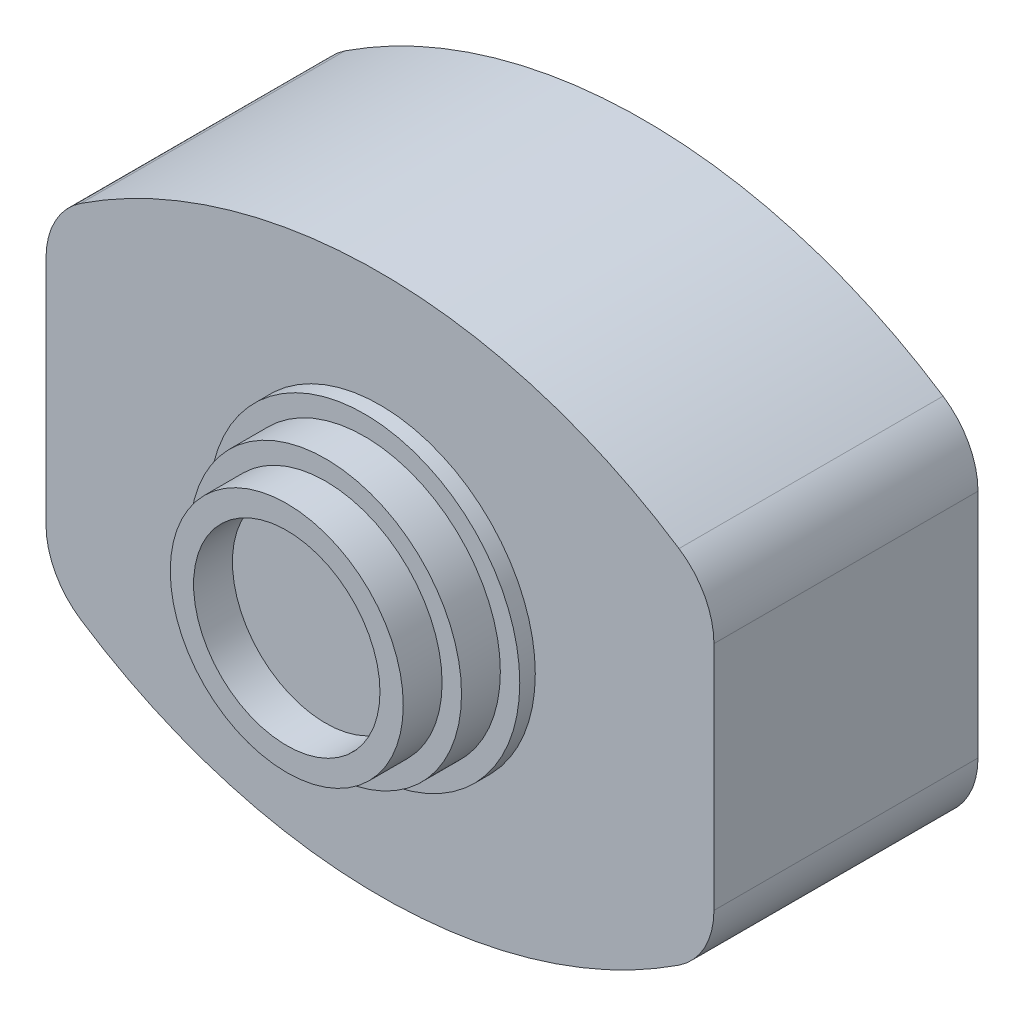
SolidWorks part; units mm, degrees
ref_plane "Front Plane" through (0, 0, 0) normal (0, 0, 1) x (1, 0, 0)
ref_plane "Top Plane" through (0, 0, 0) normal (0, 1, 0) x (1, 0, 0)
ref_plane "Right Plane" through (0, 0, 0) normal (1, 0, 0) x (0, 0, -1)
sketch "Sketch1" plane through (0, 0, 0) normal (0, 0, 1) x (1, 0, 0)
  line L1 (86, 5.126) -> (86, 34.874)
  line L3 (0, 34.874) -> (0, 5.126)
  arc A0 (4.5, 43.2257) -> (81.5, 43.2257) centre (43, -15.2359) cw
  arc A1 (4.5, -3.2257) -> (81.5, -3.2257) centre (43, 55.2359) ccw
  arc A2 (81.5, -3.2257) -> (86, 5.126) centre (76, 5.126) ccw
  arc A3 (86, 34.874) -> (81.5, 43.2257) centre (76, 34.874) ccw
  arc A4 (4.5, 43.2257) -> (0, 34.874) centre (10, 34.874) ccw
  arc A5 (4.5, -3.2257) -> (0, 5.126) centre (10, 5.126) cw
  point P15 (0, 0)
  dimension "D1" = 10
extrude "Boss-Extrude1" add sketch "Sketch1" along normal blind 34
sketch "Sketch2" plane through (0, 0, 34) normal (0, 0, 1) x (1, 0, 0)
  circle A0 centre (43, 20) radius 20
extrude "Boss-Extrude2" add sketch "Sketch2" along normal blind 2 contours A0
sketch "Sketch3" plane through (0, 0, 36) normal (0, 0, 1) x (1, 0, 0)
  circle A1 centre (43, 20) radius 17.5
extrude "Boss-Extrude3" add sketch "Sketch3" along normal blind 5
sketch "Sketch4" plane through (0, 0, 41) normal (0, 0, 1) x (1, 0, 0)
  circle A1 centre (43, 20) radius 15
extrude "Boss-Extrude4" add sketch "Sketch4" along normal blind 5
sketch "Sketch5" plane through (0, 0, 46) normal (0, 0, 1) x (1, 0, 0)
  circle A1 centre (43, 20) radius 12
extrude "Cut-Extrude1" cut sketch "Sketch5" against normal blind 5
sketch "Sketch8" plane through (0, 0, 0) normal (0, 0, -1) x (-1, 0, 0)
  line L0 (-43, 54.7641) -> (-43, -14.7641)
  line L1 (-43, -14.7641) -> (-43, 0)
  arc A0 (-4.5, 43.2257) -> (-81.5, 43.2257) centre (-43, -15.2359) ccw construction
  arc A1 (-81.5, -3.2257) -> (-4.5, -3.2257) centre (-43, 55.2359) ccw construction
ref_plane "Plane4" through (0, -14.7641, 0) normal (0, -1, 0) x (-1, 0, 0)
sketch "Sketch9" plane through (0, -14.7641, 0) normal (0, -1, 0) x (-1, 0, 0)
  line L5 (-43, -13.35) -> (-47.25, -13.35)
  line L6 (-47.25, -13.35) -> (-47.25, -19.65)
  line L7 (-46.25, -20.65) -> (-43, -20.65)
  line L8 (-43, -20.65) -> (-39.75, -20.65)
  line L9 (-38.75, -19.65) -> (-38.75, -13.35)
  line L10 (-38.75, -13.35) -> (-43, -13.35)
  line L11 (-46.25, -20.65) -> (-47.25, -19.65)
  line L15 (-39.75, -20.65) -> (-38.75, -19.65)
extrude "Cut-Extrude2" cut sketch "Sketch9" against normal blind 5
sketch "Sketch10" plane through (0, -9.7641, 0) normal (0, -1, 0) x (-1, 0, 0)
  line L4 (-41.0221, -18.7738) -> (-44.9779, -18.7738)
  line L5 (-41.0221, -18.7738) -> (-41.0221, -15.2262)
  line L6 (-41.0221, -15.2262) -> (-44.9779, -15.2262)
  line L7 (-44.9779, -18.7738) -> (-44.9779, -15.2262)
  point P6 (-43, -17)
extrude "Boss-Extrude5" add sketch "Sketch10" along normal blind 5
